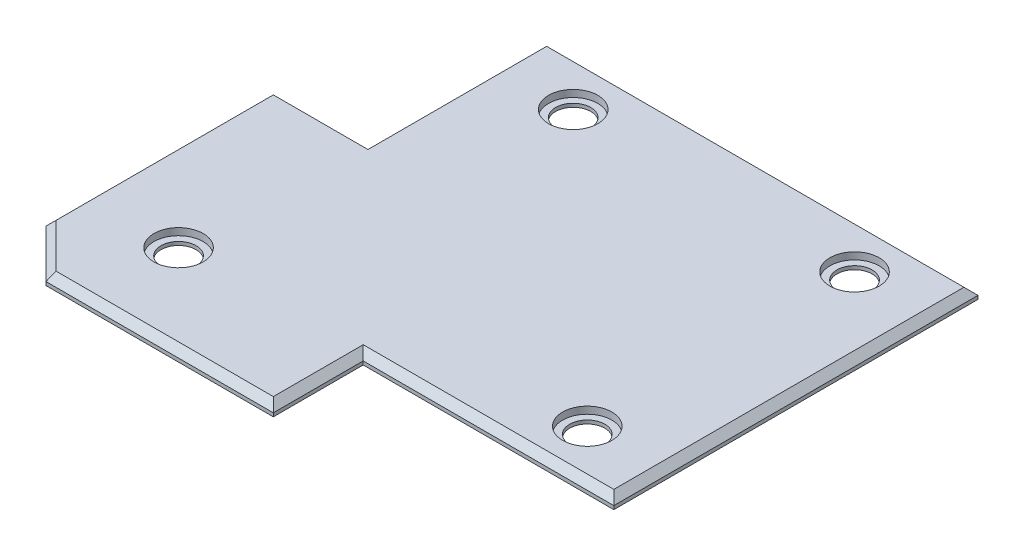
SolidWorks part; units mm, degrees
ref_plane "Front Plane" through (0, 0, 0) normal (0, 0, 1) x (1, 0, 0)
ref_plane "Top Plane" through (0, 0, 0) normal (0, 1, 0) x (1, 0, 0)
ref_plane "Right Plane" through (0, 0, 0) normal (1, 0, 0) x (0, 0, -1)
sketch "Sketch1" plane through (0, 0, 0) normal (0, 1, 0) x (1, 0, 0)
  line L1 (-1.7825, -28.3447) -> (33.8509, -28.3447)
  line L2 (-31.4806, 2.0264) -> (-31.4806, 27.4359)
  line L3 (-31.4806, 27.4359) -> (33.8509, 27.4359)
  line L4 (33.8509, -28.3447) -> (33.8509, 27.4359)
  line L7 (-44.9335, -41.1246) -> (-1.7825, -41.1246)
  line L8 (-44.9335, -41.1246) -> (-44.9335, 2.0264)
  line L9 (-44.9335, 2.0264) -> (-31.4806, 2.0264)
  line L10 (-1.7825, -41.1246) -> (-1.7825, -28.3447)
  point P0 (0, 0)
extrude "Boss-Extrude1" add sketch "Sketch1" along normal blind 2
sketch "Sketch2" plane through (0, 2, 0) normal (0, 1, 0) x (1, 0, 0)
  line L0 (-20.026, -21.3446) -> (-55.2841, -20.4558)
  line L1 (-55.2841, -20.4558) -> (-55.2841, -41.0477)
  line L2 (-55.2841, -41.0477) -> (-20.026, -21.3446)
chamfer "Chamfer1" distance 8 angle 45 1 edges at (-44.9335, 1, 41.1246)
sketch "Sketch3" plane through (0, 2, 0) normal (0, 1, 0) x (1, 0, 0)
  line L0 (-29.4806, 25.4359) -> (31.8509, 25.4359)
  line L1 (31.8509, 25.4359) -> (31.8509, -26.3447)
  line L2 (31.8509, -26.3447) -> (-3.7825, -26.3447)
  line L3 (-3.7825, -26.3447) -> (-3.7825, -39.1246)
  line L4 (-3.7825, -39.1246) -> (-36.1051, -39.1246)
  line L5 (-36.1051, -39.1246) -> (-42.9335, -32.2962)
  line L6 (-42.9335, -32.2962) -> (-42.9335, 0.0264)
  line L7 (-42.9335, 0.0264) -> (-29.4806, 0.0264)
  line L8 (-29.4806, 0.0264) -> (-29.4806, 25.4359)
  line L9 (-31.4806, 2.0264) -> (-44.9335, 2.0264) construction
  line L10 (-44.9335, 2.0264) -> (-44.9335, -33.1246) construction
  line L11 (-44.9335, -33.1246) -> (-36.9335, -41.1246) construction
  line L12 (-36.9335, -41.1246) -> (-1.7825, -41.1246) construction
  line L13 (-1.7825, -41.1246) -> (-1.7825, -28.3447) construction
  line L14 (-1.7825, -28.3447) -> (33.8509, -28.3447) construction
  line L15 (33.8509, -28.3447) -> (33.8509, 27.4359) construction
  line L16 (-31.4806, 27.4359) -> (-31.4806, 2.0264) construction
  line L17 (33.8509, 27.4359) -> (-31.4806, 27.4359) construction
  dimension "D1" = 2
  dimension "D2" = 2
  dimension "D3" = 2
  dimension "D4" = 2
  dimension "D5" = 2
  dimension "D6" = 2
  dimension "D7" = 2
  dimension "D8" = 2
  dimension "D9" = 2
extrude "Boss-Extrude2" add sketch "Sketch3" along normal blind 1.5
sketch "Sketch4" plane through (0, 0, 0) normal (0, -1, 0) x (1, 0, 0)
  line L1 (49.8844, -45.7944) -> (-49.8844, -45.7944)
  line L2 (49.8844, -45.7944) -> (49.8844, 45.7944)
  line L3 (49.8844, 45.7944) -> (-49.8844, 45.7944)
  line L4 (-49.8844, -45.7944) -> (-49.8844, 45.7944)
  line L5 (49.8844, -45.7944) -> (-49.8844, 45.7944) construction
  line L6 (49.8844, 45.7944) -> (-49.8844, -45.7944) construction
  point P0 (0, 0)
extrude "Cut-Extrude1" cut sketch "Sketch4" against normal blind 2
sketch "Sketch5" plane through (0, 3.5, 0) normal (0, 1, 0) x (1, 0, 0)
  line L0 (1.1852, 18.5456) -> (1.1852, -0.4544) construction
  line L5 (-3.7825, -26.3447) -> (31.8509, -26.3447) construction
  line L6 (31.8509, -0.4544) -> (-18.8148, -0.4544) construction
  line L7 (31.8509, -26.3447) -> (31.8509, 25.4359) construction
  line L8 (31.8509, 25.4359) -> (-29.4806, 25.4359) construction
  line L9 (-42.9335, 0.0264) -> (-42.9335, -32.2962) construction
  line L10 (21.1852, -0.4544) -> (21.1852, 18.5456) construction
  line L11 (21.1852, -19.4544) -> (1.1852, -19.4544) construction
  line L12 (21.1852, -19.4544) -> (21.1852, -0.4544) construction
  line L13 (1.1852, 18.5456) -> (-18.8148, 18.5456) construction
  line L14 (-18.8148, -19.4544) -> (-18.8148, -0.4544) construction
  line L15 (21.1852, -19.4544) -> (1.1852, -0.4544) construction
  line L16 (1.1852, -0.4544) -> (-18.8148, -19.4544) construction
  line L17 (21.1852, 18.5456) -> (1.1852, -0.4544) construction
  line L18 (21.1852, 18.5456) -> (1.1852, 18.5456) construction
  line L19 (1.1852, 25.4359) -> (1.1852, 18.5456) construction
  line L20 (1.1852, -0.4544) -> (-18.8148, 18.5456) construction
  line L21 (-18.8148, -0.4544) -> (-18.8148, 18.5456) construction
  line L22 (-18.8148, -0.4544) -> (-42.9335, -0.4544) construction
  line L23 (1.1852, -19.4544) -> (-18.8148, -19.4544) construction
  line L24 (1.1852, -0.4544) -> (1.1852, -19.4544) construction
  line L25 (1.1852, -19.4544) -> (1.1852, -26.3447) construction
  line L26 (-39.5193, -35.7104) -> (-18.8148, -16.0411) construction
  line L27 (-23.2619, -30.4944) -> (-25.7619, -30.4944) construction
  line L28 (-42.9335, -32.2962) -> (-36.1051, -39.1246) construction
  line L29 (-29.8548, -26.5291) -> (-29.8548, -16.0411) construction
  line L30 (-29.8548, -16.0411) -> (-18.8148, -16.0411) construction
  circle A0 centre (-18.8148, 18.5456) radius 2.5
  circle A1 centre (21.1852, 18.5456) radius 2.5
  circle A2 centre (21.1852, -19.4544) radius 2.5
  circle A4 centre (-29.8548, -26.5291) radius 2.5
  point P0 (0, 0)
  point P14 (1.1852, -0.4544)
  dimension "D3" = 5
  dimension "D4" = 11.04
  dimension "D1" = 40
  dimension "D2" = 38
extrude "Cut-Extrude2" cut sketch "Sketch5" against normal blind 2
sketch "Sketch8" plane through (0, 3.5, 0) normal (0, 1, 0) x (1, 0, 0)
  circle A0 centre (-18.8148, 18.5456) radius 3.5
  circle A1 centre (21.1852, 18.5456) radius 3.5
  circle A2 centre (-29.8548, -26.5291) radius 3.5
  circle A3 centre (21.1852, -19.4544) radius 3.5
  dimension "D1" = 7
extrude "Cut-Extrude3" cut sketch "Sketch8" against normal blind 1
chamfer "Chamfer2" distance 1 angle 45 9 edges at (-36.2071, 3.5, -0.0264) (-29.4806, 3.5, -12.7312) (1.1852, 3.5, -25.4359) (31.8509, 3.5, 0.4544) (14.0342, 3.5, 26.3447) (-3.7825, 3.5, 32.7346) (-19.9438, 3.5, 39.1246) (-39.5193, 3.5, 35.7104) (-42.9335, 3.5, 16.1349)
